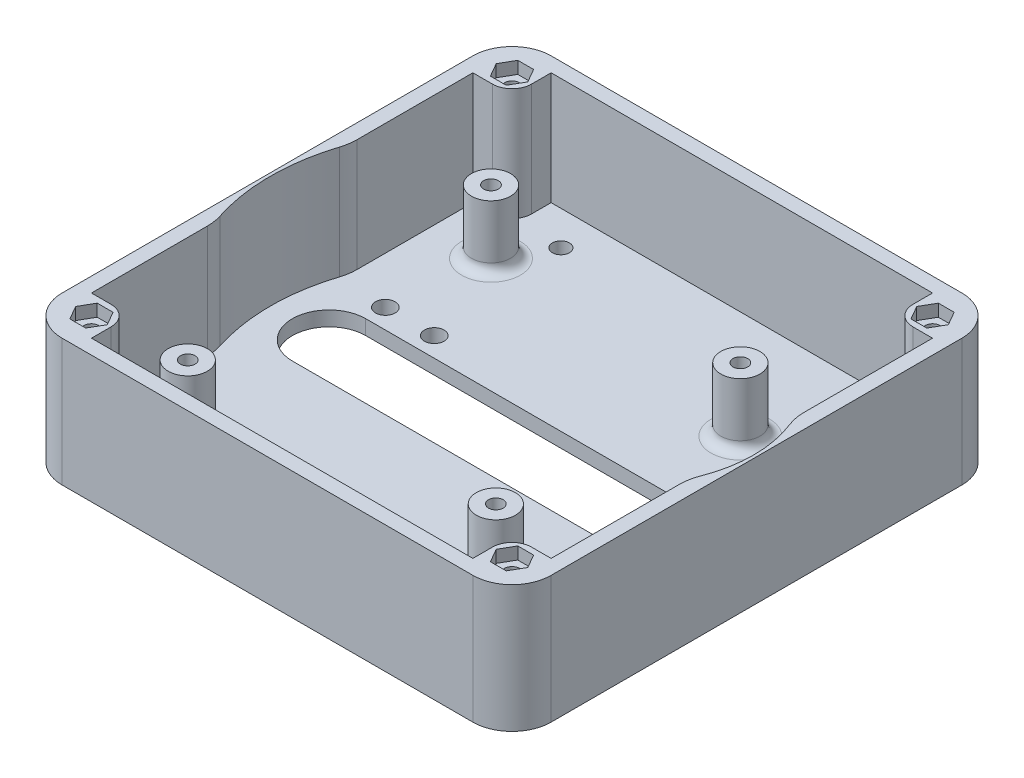
SolidWorks part; units mm, degrees
ref_plane "Спереди" through (0, 0, 0) normal (0, 0, 1) x (1, 0, 0)
ref_plane "Сверху" through (0, 0, 0) normal (0, 1, 0) x (1, 0, 0)
ref_plane "Справа" through (0, 0, 0) normal (1, 0, 0) x (0, 0, -1)
sketch "Эскиз1" plane through (0, 0, 0) normal (0, 1, 0) x (1, 0, 0)
  line L0 (0, 50) -> (100, 50) construction
  line L17 (0, 0) -> (100, 0)
  line L18 (0, 0) -> (0, 100)
  line L19 (0, 100) -> (100, 100)
  line L20 (100, 0) -> (100, 100)
  line L21 (50, 100) -> (50, 0) construction
  circle A0 centre (14.7, 81) radius 1.5
  circle A1 centre (71.7, 75) radius 1.5
  circle A2 centre (71.7, 25) radius 1.5
  circle A3 centre (14.7, 19) radius 1.5
  circle A5 centre (7, 93) radius 1.5
  circle A6 centre (93, 93) radius 1.5
  circle A7 centre (93, 7) radius 1.5
  circle A8 centre (7, 7) radius 1.5
  dimension "D3" = 3
  dimension "D8" = 3
  dimension "D1" = 100
  dimension "D2" = 100
  dimension "D4" = 62
  dimension "D5" = 50
  dimension "D6" = 57
  dimension "D7" = 28.3
  dimension "D9" = 7
  dimension "D10" = 7
extrude "Бобышка-Вытянуть1" add sketch "Эскиз1" along normal blind 3
sketch "Эскиз4" plane through (0, 3, 0) normal (0, 1, 0) x (1, 0, 0)
  line L0 (97, 97) -> (3, 97)
  line L1 (3, 97) -> (3, 65.3049)
  line L2 (3, 3) -> (97, 3)
  line L3 (97, 3) -> (97, 37.2627)
  line L4 (0, 100) -> (0, 0)
  line L5 (0, 0) -> (100, 0)
  line L6 (100, 0) -> (100, 100)
  line L7 (100, 100) -> (0, 100)
  line L8 (0, 100) -> (0, 0)
  line L9 (0, 0) -> (100, 0)
  line L10 (100, 0) -> (100, 100)
  line L11 (100, 100) -> (0, 100)
  line L12 (0, 50) -> (100, 50) construction
  line L13 (3, 34.6951) -> (3, 3)
  line L14 (3, 97) -> (3, 3) construction
  line L15 (97, 62.7373) -> (97, 97)
  line L16 (97, 3) -> (97, 97) construction
  arc A0 (2.52, 62.2439) -> (2.52, 37.7561) centre (40.6, 50) ccw
  arc A1 (97.6857, 40.9019) -> (97.6857, 59.0981) centre (74.4, 50) ccw
  arc A2 (97.6857, 59.0981) -> (97, 62.7373) centre (107, 62.7373) cw
  arc A3 (97.6857, 40.9019) -> (97, 37.2627) centre (107, 37.2627) ccw
  arc A4 (2.52, 37.7561) -> (3, 34.6951) centre (-7, 34.6951) cw
  arc A5 (2.52, 62.2439) -> (3, 65.3049) centre (-7, 65.3049) ccw
  point P12 (0.6, 50)
  point P16 (99.4, 50)
  point P20 (97, 60.6883)
  point P25 (3, 36.353)
  dimension "D4" = 80
  dimension "D6" = 50
  dimension "D7" = 10
  dimension "D3" = 0.6
  dimension "D5" = 0.6
  dimension "D1" = 0
  dimension "D2" = 3
extrude "Бобышка-Вытянуть4" add sketch "Эскиз4" along normal blind 23
sketch "Эскиз5" plane through (0, 3, 0) normal (0, 1, 0) x (1, 0, 0)
  circle A0 centre (14.7, 81) radius 4
  circle A1 centre (14.7, 81) radius 1.5 construction
  circle A2 centre (14.7, 81) radius 1.5
  circle A3 centre (14.7, 19) radius 1.5 construction
  circle A4 centre (71.7, 25) radius 1.5 construction
  circle A5 centre (71.7, 75) radius 1.5 construction
  circle A6 centre (14.7, 19) radius 1.5
  circle A7 centre (71.7, 25) radius 1.5
  circle A8 centre (71.7, 75) radius 1.5
  circle A9 centre (71.7, 75) radius 4
  circle A10 centre (71.7, 25) radius 4
  circle A11 centre (14.7, 19) radius 4
  dimension "D1" = 8
extrude "Бобышка-Вытянуть5" add sketch "Эскиз5" along normal blind 13
fillet "Скругление2" radius 2 4 edges at (14.7, 3, -23) (71.7, 3, -29) (71.7, 3, -79) (14.7, 3, -85)
fillet "Скругление3" radius 8 4 edges at (100, 13, -100) (100, 13, 0) (0, 13, 0) (0, 13, -100)
sketch "Эскиз7" plane through (0, 3, 0) normal (0, 1, 0) x (1, 0, 0)
  line L0 (3, 97) -> (3, 65.3049) construction
  line L2 (97, 97) -> (3, 97) construction
  line L6 (50, 97) -> (50, 3) construction
  line L7 (3, 3) -> (97, 3) construction
  line L8 (0, 50) -> (100, 50) construction
  line L9 (0, 92) -> (0, 8) construction
  line L10 (100, 8) -> (100, 92) construction
  line L15 (3, 89) -> (3, 97)
  line L16 (3, 97) -> (11, 97)
  line L17 (7, 89) -> (3, 89)
  line L18 (3, 97) -> (3, 65.3049) construction
  line L19 (11, 93) -> (11, 97)
  line L20 (97, 97) -> (3, 97) construction
  line L21 (89, 93) -> (89, 97)
  line L22 (93, 89) -> (97, 89)
  line L23 (97, 97) -> (89, 97)
  line L24 (97, 89) -> (97, 97)
  line L25 (97, 11) -> (97, 3)
  line L26 (97, 3) -> (89, 3)
  line L27 (93, 11) -> (97, 11)
  line L28 (89, 7) -> (89, 3)
  line L29 (11, 7) -> (11, 3)
  line L30 (7, 11) -> (3, 11)
  line L31 (3, 3) -> (11, 3)
  line L32 (3, 11) -> (3, 3)
  arc A0 (7, 89) -> (11, 93) centre (7, 93) ccw
  circle A17 centre (7, 93) radius 1.5 construction
  circle A18 centre (7, 93) radius 1.5
  circle A19 centre (93, 93) radius 1.5
  arc A20 (93, 89) -> (89, 93) centre (93, 93) cw
  arc A21 (93, 11) -> (89, 7) centre (93, 7) ccw
  circle A22 centre (93, 7) radius 1.5
  circle A23 centre (7, 7) radius 1.5
  arc A24 (7, 11) -> (11, 7) centre (7, 7) cw
extrude "Бобышка-Вытянуть6" add sketch "Эскиз7" along normal up to surface (23 mm away) up to face at (50, 26, -50)
sketch "Эскиз8" plane through (0, 3, 0) normal (0, 1, 0) x (1, 0, 0)
  line L0 (0, 50) -> (100, 50) construction
  line L1 (0, 92) -> (0, 8) construction
  line L2 (100, 8) -> (100, 92) construction
  line L3 (50, 100) -> (50, 0) construction
  line L4 (92, 100) -> (8, 100) construction
  line L5 (8, 0) -> (92, 0) construction
  line L6 (12.5921, 50) -> (87.5921, 50) construction
  line L7 (12.5921, 57.5) -> (87.5921, 57.5)
  line L8 (12.5921, 42.5) -> (87.5921, 42.5)
  arc A0 (12.5921, 57.5) -> (12.5921, 42.5) centre (12.5921, 50) ccw
  arc A1 (87.5921, 42.5) -> (87.5921, 57.5) centre (87.5921, 50) ccw
  circle A2 centre (20, 90) radius 1.75
  circle A3 centre (80, 90) radius 1.75
  circle A4 centre (80, 10) radius 1.75
  circle A5 centre (20, 10) radius 1.75
  circle A6 centre (22.5921, 61.5084) radius 2
  circle A7 centre (12.5921, 61.5084) radius 2
  point P14 (50.0921, 50)
  dimension "D3" = 3.5
  dimension "D6" = 4
  dimension "D1" = 15
  dimension "D2" = 75
  dimension "D4" = 60
  dimension "D5" = 80
  dimension "D7" = 10
extrude "Вырез-Вытянуть2" cut sketch "Эскиз8" against normal up to surface (3 mm away) up to face at (93, 0, -5.5)
sketch "Эскиз9" plane through (0, 0, 0) normal (0, -1, 0) x (1, 0, 0)
  circle A0 centre (7, -7) radius 3.25
  circle A1 centre (93, -7) radius 3.25
  circle A2 centre (93, -93) radius 3.25
  circle A3 centre (7, -93) radius 3.25
  dimension "D1" = 6.5
extrude "Вырез-Вытянуть3" cut sketch "Эскиз9" against normal blind 2.5
sketch "Эскиз10" plane through (0, 26, 0) normal (0, 1, 0) x (1, 0, 0)
  line L0 (0, 50) -> (100, 50) construction
  line L1 (8.6166, 90.2) -> (10.2332, 93)
  line L2 (10.2332, 93) -> (8.6166, 95.8)
  line L3 (8.6166, 95.8) -> (5.3834, 95.8)
  line L4 (5.3834, 95.8) -> (3.7668, 93)
  line L5 (3.7668, 93) -> (5.3834, 90.2)
  line L6 (5.3834, 90.2) -> (8.6166, 90.2)
  line L7 (0, 92) -> (0, 8) construction
  line L8 (100, 8) -> (100, 92) construction
  line L9 (50, 100) -> (50, 0) construction
  line L10 (92, 100) -> (8, 100) construction
  line L11 (8, 0) -> (92, 0) construction
  line L30 (94.6166, 90.2) -> (91.3834, 90.2)
  line L31 (96.2332, 93) -> (94.6166, 90.2)
  line L32 (94.6166, 95.8) -> (96.2332, 93)
  line L33 (91.3834, 95.8) -> (94.6166, 95.8)
  line L34 (89.7668, 93) -> (91.3834, 95.8)
  line L35 (91.3834, 90.2) -> (89.7668, 93)
  line L36 (91.3834, 9.8) -> (89.7668, 7)
  line L37 (89.7668, 7) -> (91.3834, 4.2)
  line L38 (91.3834, 4.2) -> (94.6166, 4.2)
  line L39 (94.6166, 4.2) -> (96.2332, 7)
  line L40 (96.2332, 7) -> (94.6166, 9.8)
  line L41 (94.6166, 9.8) -> (91.3834, 9.8)
  line L42 (5.3834, 9.8) -> (8.6166, 9.8)
  line L43 (3.7668, 7) -> (5.3834, 9.8)
  line L44 (5.3834, 4.2) -> (3.7668, 7)
  line L45 (8.6166, 4.2) -> (5.3834, 4.2)
  line L46 (10.2332, 7) -> (8.6166, 4.2)
  line L47 (8.6166, 9.8) -> (10.2332, 7)
  circle A0 centre (7, 93) radius 2.8 construction
  circle A1 centre (93, 93) radius 2.8 construction
  circle A2 centre (93, 7) radius 2.8 construction
  circle A3 centre (7, 7) radius 2.8 construction
  point P1 (7, 90.2)
  point P22 (50, 50)
  point P50 (50, 50)
  dimension "D1" = 5.6
extrude "Вырез-Вытянуть4" cut sketch "Эскиз10" against normal blind 2.5
